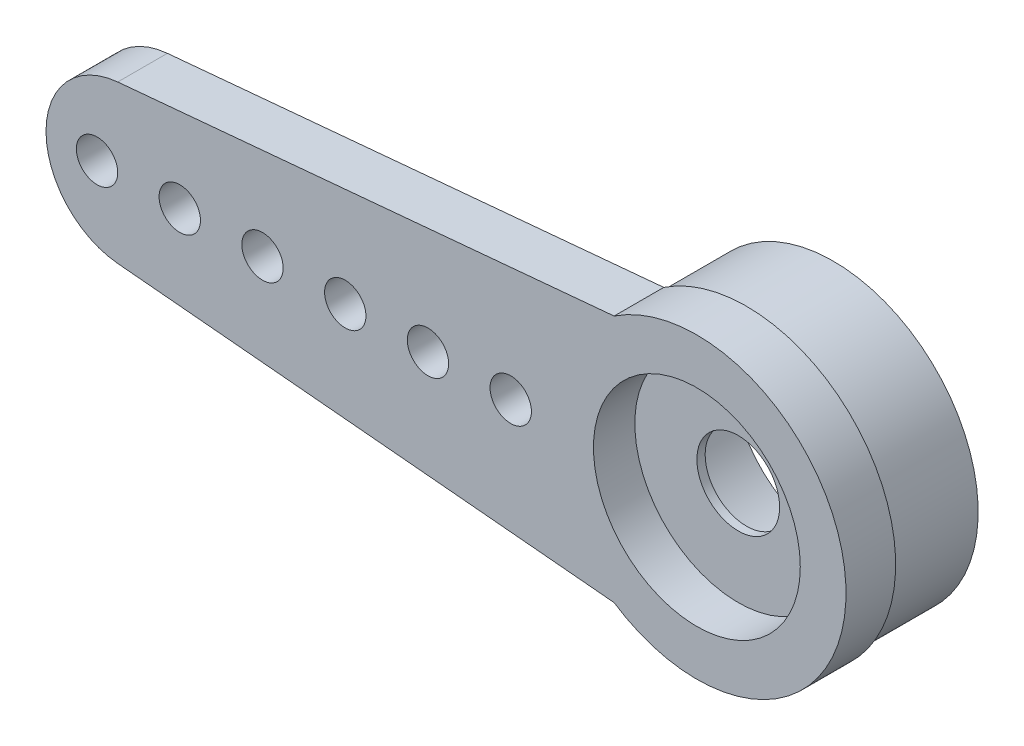
SolidWorks part; units mm, degrees
ref_plane "Front Plane" through (0, 0, 0) normal (0, 0, 1) x (1, 0, 0)
ref_plane "Top Plane" through (0, 0, 0) normal (0, 1, 0) x (1, 0, 0)
ref_plane "Right Plane" through (0, 0, 0) normal (1, 0, 0) x (0, 0, -1)
sketch "Sketch1" plane through (0, 0, 0) normal (0, 0, 1) x (1, 0, 0)
  line L0 (2, 0) -> (14, 0) construction
  line L2 (-2, -6.75) -> (-2, -3)
  line L4 (2, -6.75) -> (2, -3)
  line L5 (-2, -6.75) -> (2, 6.75) construction
  line L6 (-2, 6.75) -> (2, -6.75) construction
  line L7 (2, 0) -> (2, 3) construction
  line L8 (2, 0) -> (2, -3) construction
  line L9 (14, 0) -> (14, 1.9) construction
  line L10 (14, 0) -> (14, -1.9) construction
  line L11 (2, 3) -> (14, 1.9)
  line L12 (14, -1.9) -> (2, -3)
  line L13 (2, 3) -> (2, 6.75)
  line L14 (-2, 0) -> (-2, 3) construction
  line L15 (-2, 0) -> (-2, -3) construction
  line L16 (-2, 0) -> (-14, 0) construction
  line L17 (-14, 0) -> (-14, 1.9) construction
  line L18 (-14, 0) -> (-14, -1.9) construction
  line L19 (-14, 1.9) -> (-2, 3)
  line L20 (-14, -1.9) -> (-2, -3)
  line L21 (-2, 3) -> (-2, 6.75)
  arc A0 (-2, 6.75) -> (2, 6.75) centre (0, 6.75) cw
  arc A1 (2, -6.75) -> (-2, -6.75) centre (0, -6.75) cw
  arc A2 (14, -1.9) -> (14, 1.9) centre (13.8258, 0) ccw
  arc A3 (-14, 1.9) -> (-14, -1.9) centre (-13.8258, 0) ccw
  point P0 (0, 0)
  dimension "D1" = 4
  dimension "D2" = 13.5
  dimension "D3" = 12
  dimension "D4" = 3
  dimension "D5" = 3
  dimension "D6" = 1.9
  dimension "D7" = 1.9
  dimension "D8" = 3
  dimension "D9" = 3
  dimension "D10" = 12
  dimension "D11" = 1.9
  dimension "D12" = 1.9
extrude "Boss-Extrude1" add sketch "Sketch1" along normal blind 1.2
sketch "Sketch2" plane through (0, 0, 0) normal (0, 0, -1) x (-1, 0, 0)
  line L0 (-2, 3) -> (-2, -3) construction
  line L1 (2, -3) -> (2, 3) construction
  line L2 (2, 0) -> (-2, 0) construction
  circle A0 centre (0, 0) radius 3.5
  dimension "D1" = 7
extrude "Boss-Extrude2" add sketch "Sketch2" along normal blind 2.1
sketch "Sketch3" plane through (0, 0, 1.2) normal (0, 0, 1) x (1, 0, 0)
  line L0 (-2, 3) -> (-2, -3) construction
  line L1 (2, -3) -> (2, 3) construction
  line L2 (2, 0) -> (-2, 0) construction
  circle A0 centre (0, 0) radius 2.5
  dimension "D1" = 5
extrude "Cut-Extrude1" cut sketch "Sketch3" against normal blind 1
sketch "Sketch4" plane through (0, 0, 0.2) normal (0, 0, 1) x (1, 0, 0)
  circle A0 centre (0, 0) radius 1
  dimension "D1" = 2
extrude "Cut-Extrude2" cut sketch "Sketch4" against normal through all
sketch "Sketch6" plane through (0, 0, -2.1) normal (0, 0, -1) x (-1, 0, 0)
  circle A0 centre (0, 0) radius 2.45
  dimension "D1" = 4.9
extrude "Cut-Extrude3" cut sketch "Sketch6" against normal blind 2.1
sketch "Sketch8" plane through (0, 0, 1.2) normal (0, 0, 1) x (1, 0, 0)
  line L0 (4.5, 0) -> (-4.5, 0) construction
  line L1 (-4.5, 0) -> (-6.5, 0) construction
  line L2 (-6.5, 0) -> (-8.5, 0) construction
  line L3 (-8.5, 0) -> (-10.5, 0) construction
  line L4 (-10.5, 0) -> (-12.5, 0) construction
  line L5 (-12.5, 0) -> (-14.5, 0) construction
  line L6 (0, 0) -> (0, -0.466) construction
  circle A0 centre (-4.5, 0) radius 0.5
  circle A1 centre (-6.5, 0) radius 0.5
  circle A2 centre (-8.5, 0) radius 0.5
  circle A3 centre (-10.5, 0) radius 0.5
  circle A4 centre (-12.5, 0) radius 0.5
  circle A5 centre (-14.5, 0) radius 0.5
  dimension "D7" = 1
  dimension "D8" = 1
  dimension "D9" = 1
  dimension "D10" = 1
  dimension "D11" = 1
  dimension "D12" = 1
  dimension "D1" = 4.5
  dimension "D2" = 2
  dimension "D3" = 2
  dimension "D4" = 2
  dimension "D5" = 2
  dimension "D6" = 2
extrude "Cut-Extrude5" cut sketch "Sketch8" against normal through all
sketch "Sketch10" plane through (0, 0, 0) normal (0, 0, -1) x (-1, 0, 0)
  line L0 (2, 6.75) -> (2, 3) construction
  line L1 (14, -1.9) -> (2, -3) construction
  line L2 (-2, 3) -> (-3.5, 8.058)
  line L3 (-3.5, 8.058) -> (0.4107, 10.2637)
  line L4 (0.4107, 10.2637) -> (4.9724, 6.3286)
  line L5 (4.9724, 6.3286) -> (2, 3)
  line L6 (-2, -3) -> (-3.7991, -6.6528)
  line L7 (-3.7991, -6.6528) -> (-0.6308, -10.284)
  line L8 (-0.6308, -10.284) -> (2.5658, -9.7876)
  line L9 (2.5658, -9.7876) -> (3.7316, -4.8264)
  line L10 (3.7316, -4.8264) -> (2, -3)
  arc A0 (-2, 3) -> (2, 3) centre (0, 0) cw
  arc A1 (-2, -3) -> (2, -3) centre (0, 0) ccw
extrude "Cut-Extrude6" cut sketch "Sketch10" against normal blind 10
sketch "Sketch11" plane through (0, 0, 1.2) normal (0, 0, 1) x (1, 0, 0)
sketch "Sketch12" plane through (0, 0, 0) normal (0, 0, -1) x (-1, 0, 0)
  line L0 (-2, -3) -> (-14, -1.9) construction
  line L1 (-14, 1.9) -> (-2, 3)
  line L2 (-14, -1.9) -> (-2, -3)
  arc A0 (-2, 3) -> (-2, -3) centre (0, 0) ccw
  arc A1 (-14, 1.9) -> (-14, -1.9) centre (-13.8258, 0) ccw
  arc A2 (-14, 1.9) -> (-14, -1.9) centre (-13.8258, 0) ccw construction
extrude "Cut-Extrude7" cut sketch "Sketch12" against normal blind 10
